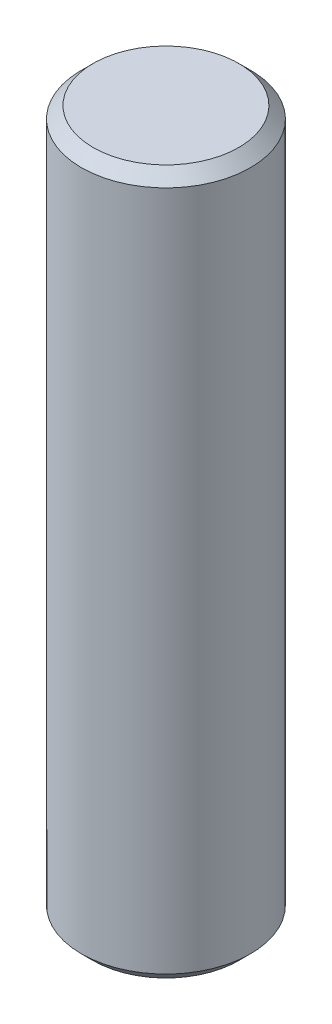
SolidWorks part; units mm, degrees
material "Простая углеродистая сталь"
ref_plane "Спереди" through (0, 0, 0) normal (0, 0, 1) x (1, 0, 0)
ref_plane "Сверху" through (0, 0, 0) normal (0, 1, 0) x (1, 0, 0)
ref_plane "Справа" through (0, 0, 0) normal (1, 0, 0) x (0, 0, -1)
sketch "Эскиз1" plane through (0, 0, 0) normal (0, 1, 0) x (1, 0, 0)
  circle A0 centre (0, 0) radius 6
  dimension "D1" = 12
extrude "Бобышка-Вытянуть1" add sketch "Эскиз1" along normal blind 50
cosmetic thread "Условное изображение резьбы1" parameters "D1"=15, "D2"=10.344
cosmetic thread "Условное изображение резьбы2" parameters "D1"=15, "D2"=10.344
chamfer "Фаска1" distance 0.828 angle 45 2 edges at (0, 0, 6) (0, 50, 6)
